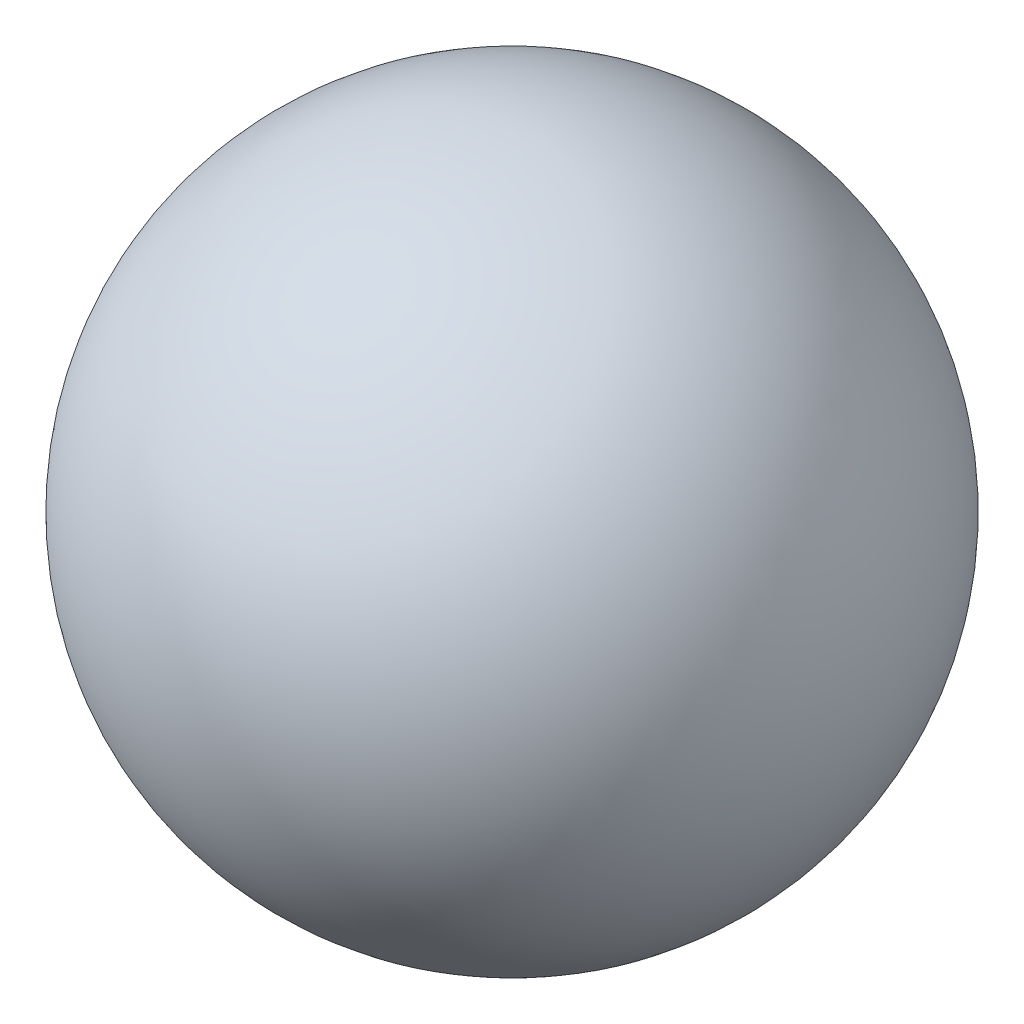
SolidWorks part; units mm, degrees
other "Markup1"
sketch "Sketch6" plane through (114.3, 38.1, 139.7) normal (0.0122, 0.8279, 0.5607) x (0.9984, -0.0412, 0.0392)
material "Glass"
ref_plane "Front Plane" through (0, 0, 0) normal (0, 0, 1) x (1, 0, 0)
ref_plane "Top Plane" through (0, 0, 0) normal (0, 1, 0) x (1, 0, 0)
ref_plane "Right Plane" through (0, 0, 0) normal (1, 0, 0) x (0, 0, -1)
sketch "Sketch7" plane through (0, 0, 0) normal (0, 0, 1) x (1, 0, 0)
  line L0 (0, 6.35) -> (0, -6.35)
  arc A0 (0, -6.35) -> (0, 6.35) centre (0, 0) ccw
  dimension "D1" = 12.7
revolve "Revolve1" add sketch "Sketch7" angle 360 about L0
